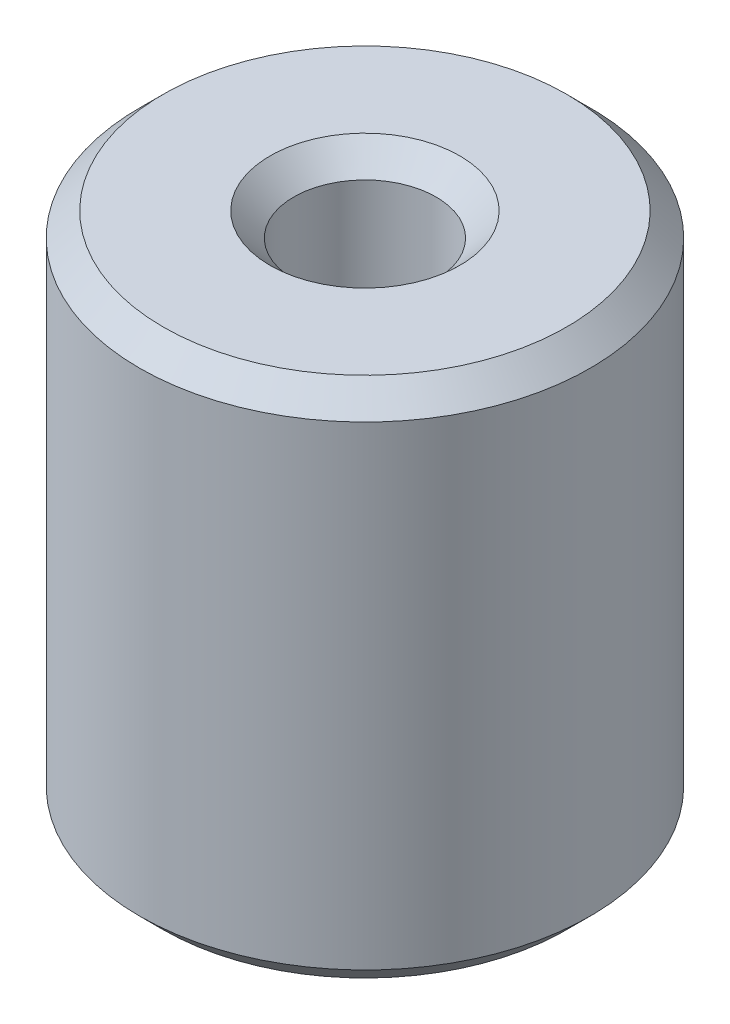
SolidWorks part; units mm, degrees
ref_plane "Front Plane" through (0, 0, 0) normal (0, 0, 1) x (1, 0, 0)
ref_plane "Top Plane" through (0, 0, 0) normal (0, 1, 0) x (1, 0, 0)
ref_plane "Right Plane" through (0, 0, 0) normal (1, 0, 0) x (0, 0, -1)
sketch "Sketch1" plane through (0, 0, 0) normal (0, 1, 0) x (1, 0, 0)
  circle A0 centre (0, 0) radius 3
  circle A1 centre (0, 0) radius 9.5
  dimension "D1" = 19
  dimension "D2" = 6
extrude "Boss-Extrude1" add sketch "Sketch1" along normal blind 22
chamfer "Chamfer1" distance 1 angle 45 4 edges at (0, 0, 3) (0, 0, 9.5) (0, 22, 3) (0, 22, 9.5)
